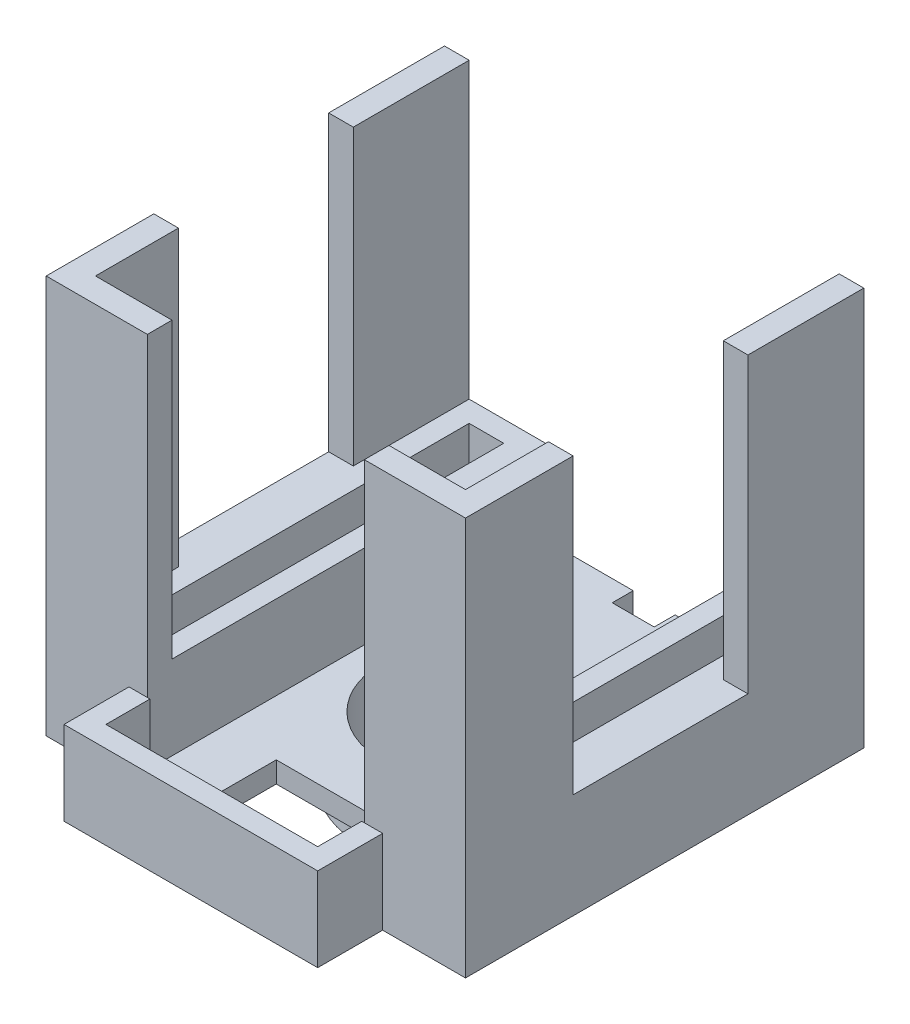
SolidWorks part; units mm, degrees
ref_plane "Front Plane" through (0, 0, 0) normal (0, 0, 1) x (1, 0, 0)
ref_plane "Top Plane" through (0, 0, 0) normal (0, 1, 0) x (1, 0, 0)
ref_plane "Right Plane" through (0, 0, 0) normal (1, 0, 0) x (0, 0, -1)
sketch "Sketch1" plane through (0, 0, 0) normal (0, 1, 0) x (1, 0, 0)
  line L1 (40, -2) -> (40, -40)
  line L2 (40, -40) -> (0, -40)
  line L4 (0, -2) -> (0, -40)
  line L7 (2.35, -20) -> (2.35, -2.35)
  line L9 (37.65, -2.35) -> (37.65, -20)
  line L10 (37.65, -20) -> (37.65, -37.65)
  line L11 (37.65, -37.65) -> (2.35, -37.65)
  line L12 (2.35, -37.65) -> (2.35, -20)
  line L18 (2.35, -2) -> (0, -2)
  line L19 (2.35, -2) -> (2.35, -2.35)
  line L20 (37.65, -2) -> (37.65, -2.35)
  line L21 (37.65, -2) -> (40, -2)
extrude "Boss-Extrude2" add sketch "Sketch1" along normal blind 28
sketch "Sketch3" plane through (0, 0, 0) normal (0, -1, 0) x (1, 0, 0)
  line L1 (0, 40) -> (40, 40)
  line L2 (0, 40) -> (0, 2)
  line L3 (0, 2) -> (40, 2)
  line L4 (40, 40) -> (40, 2)
extrude "Boss-Extrude3" add sketch "Sketch3" along normal blind 10
sketch "Sketch5" plane through (0, 0, 0) normal (0, 1, 0) x (1, 0, 0)
  line L0 (9.65, -20) -> (9.65, -57.9)
  line L1 (2.35, -2) -> (37.65, -2) construction
  line L2 (9.65, -2) -> (30.35, -2)
  line L5 (30.35, -20) -> (30.35, -2)
  line L6 (9.65, -2) -> (9.65, -20)
  line L7 (9.65, -57.9) -> (20, -57.9)
  line L8 (20, -57.9) -> (30.35, -57.9)
  line L9 (30.35, -57.9) -> (30.35, -20)
extrude "Cut-Extrude2" cut sketch "Sketch5" against normal blind 8
sketch "Sketch6" plane through (0, -8, 0) normal (0, 1, 0) x (1, 0, 0)
  line L1 (9.65, -2) -> (30.35, -2)
  line L2 (9.65, -2) -> (9.65, -40)
  line L3 (9.65, -40) -> (30.35, -40)
  line L4 (30.35, -2) -> (30.35, -40)
extrude "Cut-Extrude3" cut sketch "Sketch6" along normal blind 43
sketch "Sketch7" plane through (0, -8, 0) normal (0, 1, 0) x (1, 0, 0)
  line L1 (30.35, -2) -> (9.65, -2) construction
  line L2 (20, -4) -> (18, -4)
  line L3 (18, -4) -> (18, -2)
  line L4 (18, -2) -> (22, -2)
  line L5 (22, -2) -> (22, -4)
  line L6 (22, -4) -> (20, -4)
extrude "Cut-Extrude4" cut sketch "Sketch7" against normal blind 43
sketch "Sketch9" plane through (0, -10, 0) normal (0, -1, 0) x (1, 0, 0)
  line L4 (30.1, 44.2) -> (30.1, 40)
  line L5 (40, 40) -> (0, 40) construction
  line L6 (9.9, 44.2) -> (9.9, 40)
  line L8 (32.1, 46.2) -> (32.1, 40)
  line L10 (7.9, 46.2) -> (7.9, 40)
  line L13 (18, 46.2) -> (9.9, 46.2)
  line L14 (7.9, 40) -> (9.9, 40)
  line L15 (7.9, 38) -> (32.1, 38) construction
  line L16 (7.9, 58.3) -> (7.9, 38) construction
  line L17 (32.1, 58.3) -> (32.1, 38) construction
  line L18 (30.1, 40) -> (32.1, 40)
  line L19 (9.9, 46.2) -> (7.9, 46.2)
  line L20 (9.9, 40) -> (30.1, 40) construction
  line L21 (18, 46.2) -> (32.1, 46.2)
  line L23 (9.9, 56.3) -> (9.9, 40) construction
  line L24 (20, 56.3) -> (9.9, 56.3) construction
  line L25 (20, 58.3) -> (7.9, 58.3) construction
  line L26 (20, 56.3) -> (30.1, 56.3) construction
  line L27 (20, 58.3) -> (32.1, 58.3) construction
  line L28 (30.1, 56.3) -> (30.1, 40) construction
  line L29 (9.9, 44.2) -> (30.1, 44.2)
extrude "Boss-Extrude5" add sketch "Sketch9" against normal blind 8
sketch "Sketch10" plane through (0, -10, 0) normal (0, -1, 0) x (1, 0, 0)
  circle A0 centre (20, 20) radius 10
extrude "Boss-Extrude6" add sketch "Sketch10" along normal blind 4
sketch "Sketch11" plane through (0, -14, 0) normal (0, -1, 0) x (-1, 0, 0)
  circle A0 centre (-20, -20) radius 8
extrude "Cut-Extrude5" cut sketch "Sketch11" against normal blind 4
sketch "Sketch12" plane through (0, -10, 0) normal (0, -1, 0) x (1, 0, 0)
  circle A0 centre (20, 20) radius 8
extrude "Cut-Extrude6" cut sketch "Sketch12" against normal blind 10
sketch "Sketch13" plane through (0, 0, 0) normal (0, 1, 0) x (1, 0, 0)
  line L0 (4.35, -35.65) -> (4.35, -4)
  line L5 (4.35, -4) -> (7.65, -4)
  line L6 (7.65, -35.65) -> (7.65, -4)
  line L7 (4.35, -35.65) -> (7.65, -35.65)
extrude "Cut-Extrude7" cut sketch "Sketch13" against normal blind 10
sketch "Sketch14" plane through (0, 0, 0) normal (0, 1, 0) x (1, 0, 0)
  line L0 (32.35, -35.65) -> (32.35, -4)
  line L5 (32.35, -4) -> (35.65, -4)
  line L6 (35.65, -35.65) -> (35.65, -4)
  line L7 (32.35, -35.65) -> (35.65, -35.65)
extrude "Cut-Extrude8" cut sketch "Sketch14" against normal blind 10
sketch "Sketch15" plane through (40, 0, 0) normal (1, 0, 0) x (0, 0, -1)
  line L0 (-40, 28) -> (-2, 28) construction
  line L1 (-29.7328, 28) -> (-13.0529, 28)
  line L2 (-29.7328, 28) -> (-29.7328, 0)
  line L3 (-29.7328, 0) -> (-13.0529, 0)
  line L4 (-13.0529, 28) -> (-13.0529, 0)
extrude "Cut-Extrude9" cut sketch "Sketch15" against normal blind 253
sketch "Sketch16" plane through (0, -10, 0) normal (0, -1, 0) x (1, 0, 0)
  line L2 (14.95, 33) -> (25.05, 33)
  line L4 (14.95, 40) -> (25.05, 40)
  line L6 (14.95, 33) -> (14.95, 40)
  line L7 (25.05, 40) -> (25.05, 33)
extrude "Cut-Extrude11" cut sketch "Sketch16" against normal blind 13
